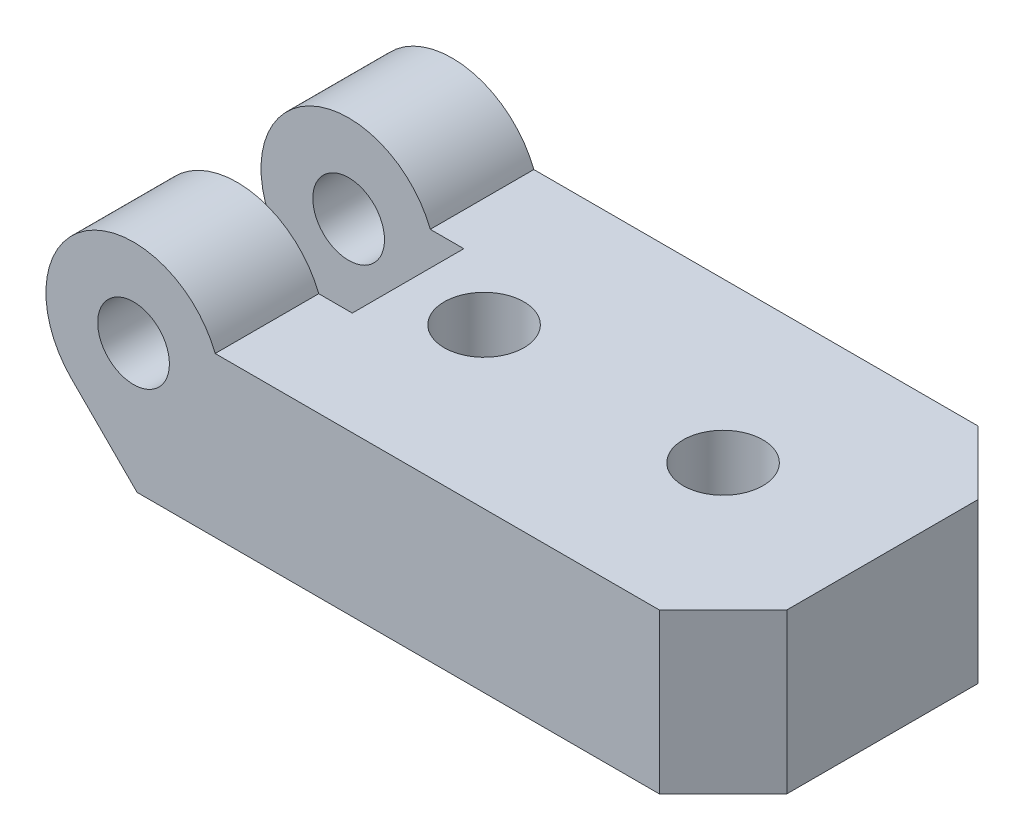
SolidWorks part; units mm, degrees
material "Printed PLA"
ref_plane "Front Plane" through (0, 0, 0) normal (0, 0, 1) x (1, 0, 0)
ref_plane "Top Plane" through (0, 0, 0) normal (0, 1, 0) x (1, 0, 0)
ref_plane "Right Plane" through (0, 0, 0) normal (1, 0, 0) x (0, 0, -1)
sketch "Sketch1" plane through (0, 0, 0) normal (0, 1, 0) x (1, 0, 0)
  line L0 (-25, 0) -> (-10, 0) construction
  line L1 (-35, 10) -> (0, 10)
  line L2 (-35, 10) -> (-35, -10)
  line L3 (-35, -10) -> (0, -10)
  line L4 (0, 10) -> (0, -10)
  line L5 (-10, 0) -> (0, 0) construction
  circle A0 centre (-10, 0) radius 2.5
  circle A1 centre (-25, 0) radius 2.5
  dimension "D4" = 5
  dimension "D5" = 10
  dimension "D1" = 20
  dimension "D2" = 15
  dimension "D3" = 10
extrude "Boss-Extrude1" add sketch "Sketch1" along normal blind 10
sketch "Sketch2" plane through (0, 0, 10) normal (0, 0, 1) x (1, 0, 0)
  line L0 (-35, 0) -> (0, 0) construction
  line L1 (-35, 10) -> (-35, 0) construction
  line L2 (-35, 0) -> (-36.7782, 0)
  line L3 (-35, 0) -> (-35, 2.8765)
  line L4 (-36.7782, 0) -> (-40.8891, 4.1109)
  arc A0 (-35, 2.8765) -> (-40.8891, 4.1109) centre (-37, 8) ccw
  dimension "D1" = 11
  dimension "D2" = 8
  dimension "D3" = 2
  dimension "D4" = 45
extrude "Boss-Extrude2" add sketch "Sketch2" against normal offset from surface (6.5 mm away) 3.5 up to plane "Front Plane"
mirror "Mirror1" about plane through (0, 0, 0) normal (0, 0, 1) of "Boss-Extrude2"
sketch "Sketch3" plane through (0, 0, -3.5) normal (0, 0, 1) x (1, 0, 0)
  circle A0 centre (-37, 8) radius 7.5
  dimension "D1" = 15
extrude "Cut-Extrude1" cut sketch "Sketch3" along normal up to surface (7 mm away) up to face at (-36.6339, 5.9319, 3.5)
sketch "Sketch4" plane through (0, 0, 10) normal (0, 0, 1) x (1, 0, 0)
  circle A0 centre (-37, 8) radius 2.25
  dimension "D1" = 4.5
extrude "Cut-Extrude2" cut sketch "Sketch4" against normal through all
chamfer "Chamfer1" distance 4 angle 45 2 edges at (0, 5, -10) (0, 5, 10)
